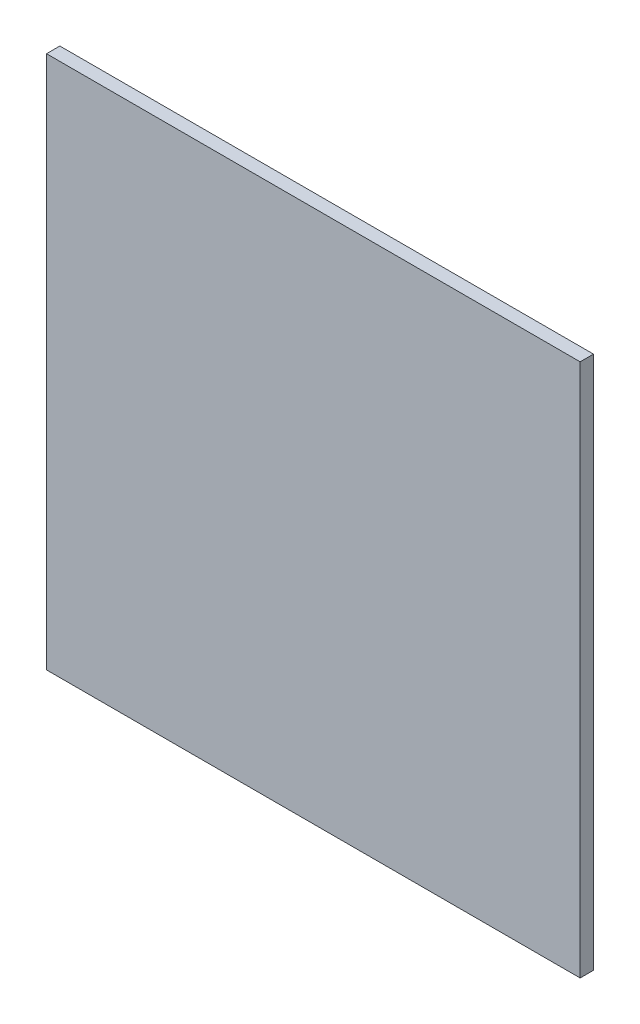
SolidWorks part; units mm, degrees
ref_plane "Plan de face" through (0, 0, 0) normal (0, 0, 1) x (1, 0, 0)
ref_plane "Plan de dessus" through (0, 0, 0) normal (0, 1, 0) x (1, 0, 0)
ref_plane "Plan de droite" through (0, 0, 0) normal (1, 0, 0) x (0, 0, -1)
sketch "Esquisse1" plane through (0, 0, 0) normal (0, 0, 1) x (1, 0, 0)
  line L1 (-200, -200) -> (200, -200)
  line L2 (-200, -200) -> (-200, 200)
  line L3 (-200, 200) -> (200, 200)
  line L4 (200, -200) -> (200, 200)
  line L5 (-200, -200) -> (200, 200) construction
  line L6 (-200, 200) -> (200, -200) construction
  point P0 (0, 0)
  point P19 (0, 0)
  point P20 (0, 0)
  dimension "D1" = 400
  dimension "D2" = 400
extrude "Boss.-Extru.1" add sketch "Esquisse1" along normal blind 10
sketch "Esquisse9" plane through (0, 0, 10) normal (0, 0, 1) x (1, 0, 0)
  line L0 (-125, 200) -> (-125, 130) construction
  line L1 (200, 200) -> (-200, 200) construction
  line L2 (-125, 130) -> (-200, 130) construction
  line L3 (-200, 200) -> (-200, -200) construction
  line L4 (-125, 130) -> (-125, 5) construction
  line L5 (-125, 5) -> (-125, 51.3985) construction
  line L6 (-125, 5) -> (-125, -120) construction
  circle A0 centre (-125, 130) radius 3.7807
  circle A1 centre (-125, 5) radius 1.8072
  circle A2 centre (-125, -120) radius 2.9752
  dimension "D1" = 70
  dimension "D2" = 75
  dimension "D3" = 125
  dimension "D4" = 125
